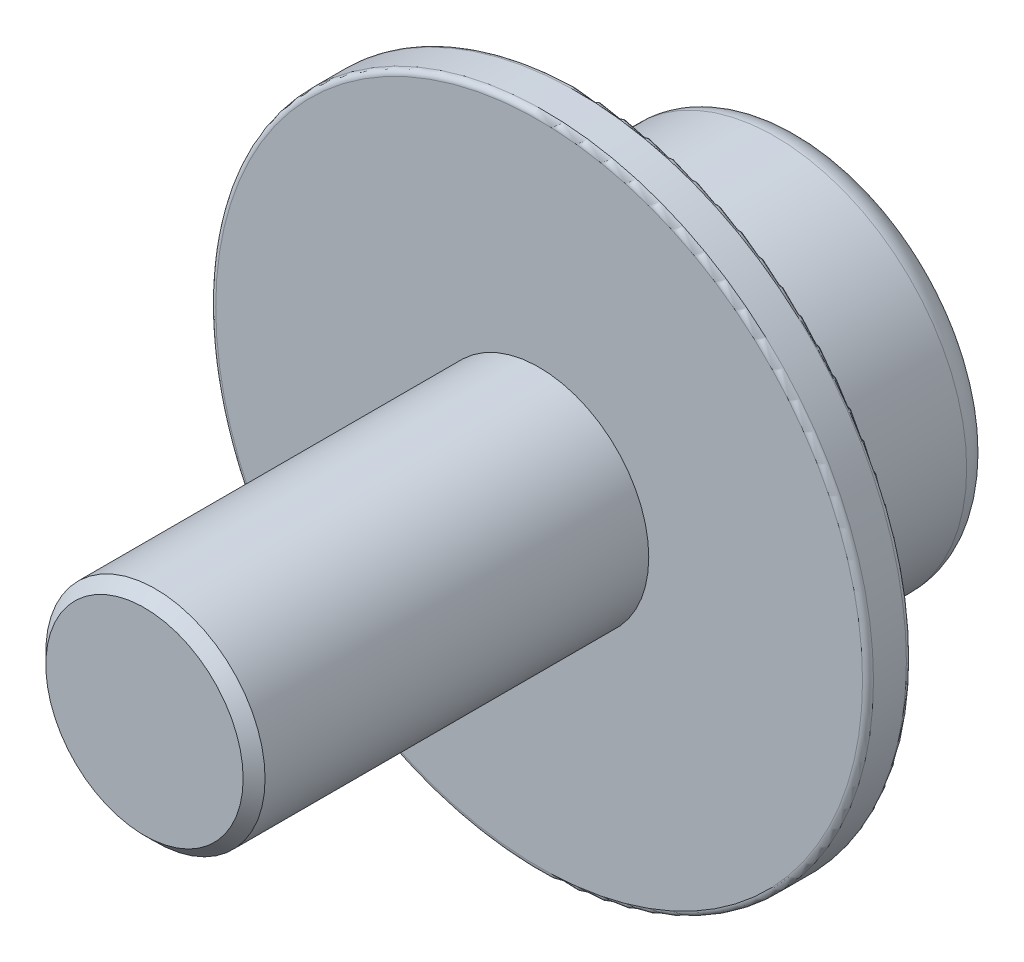
SolidWorks part; units mm, degrees
material "AISI 4340 Steel, annealed"
ref_plane "Front Plane" through (0, 0, 0) normal (0, 0, 1) x (1, 0, 0)
ref_plane "Top Plane" through (0, 0, 0) normal (0, 1, 0) x (1, 0, 0)
ref_plane "Right Plane" through (0, 0, 0) normal (1, 0, 0) x (0, 0, -1)
sketch "Sketch1" plane through (0, 0, 0) normal (0, 0, 1) x (1, 0, 0)
  circle A0 centre (0, 0) radius 3.5
  dimension "D1" = 7
extrude "Boss-Extrude1" add sketch "Sketch1" along normal blind 4
sketch "Sketch2" plane through (0, 0, 4) normal (0, 0, 1) x (1, 0, 0)
  circle A0 centre (0, 0) radius 2
  dimension "D1" = 4
extrude "Boss-Extrude2" add sketch "Sketch2" along normal blind 8
sketch "Sketch3" plane through (0, 0, 0) normal (0, 0, -1) x (-1, 0, 0)
  line L1 (2.0207, 0) -> (1.0104, 1.75)
  line L2 (1.0104, 1.75) -> (-1.0104, 1.75)
  line L3 (-1.0104, 1.75) -> (-2.0207, 0)
  line L4 (-2.0207, 0) -> (-1.0104, -1.75)
  line L5 (-1.0104, -1.75) -> (1.0104, -1.75)
  line L6 (1.0104, -1.75) -> (2.0207, 0)
  circle A0 centre (0, 0) radius 1.75 construction
  dimension "D1" = 3.5
extrude "Cut-Extrude1" cut sketch "Sketch3" against normal blind 2.5
fillet "Fillet1" radius 0.5 9 edges at (3.5, 0, 4) (2, 0, 4) (3.5, 0, 0) (0, 1.75, 0) (1.5155, 0.875, 0) (1.5155, -0.875, 0) (0, -1.75, 0) (-1.5155, -0.875, 0) (-1.5155, 0.875, 0)
chamfer "Chamfer1" distance 0.2 angle 45 1 edges at (2, 0, 12)
sketch "Sketch4" plane through (0, 0, 4) normal (0, 0, 1) x (1, 0, 0)
  circle A0 centre (0, 0) radius 6
  dimension "D1" = 12
extrude "Boss-Extrude3" add sketch "Sketch4" along normal blind 0.8
fillet "Fillet2" radius 0.1 2 edges at (6, 0, 4.8) (6, 0, 4)
